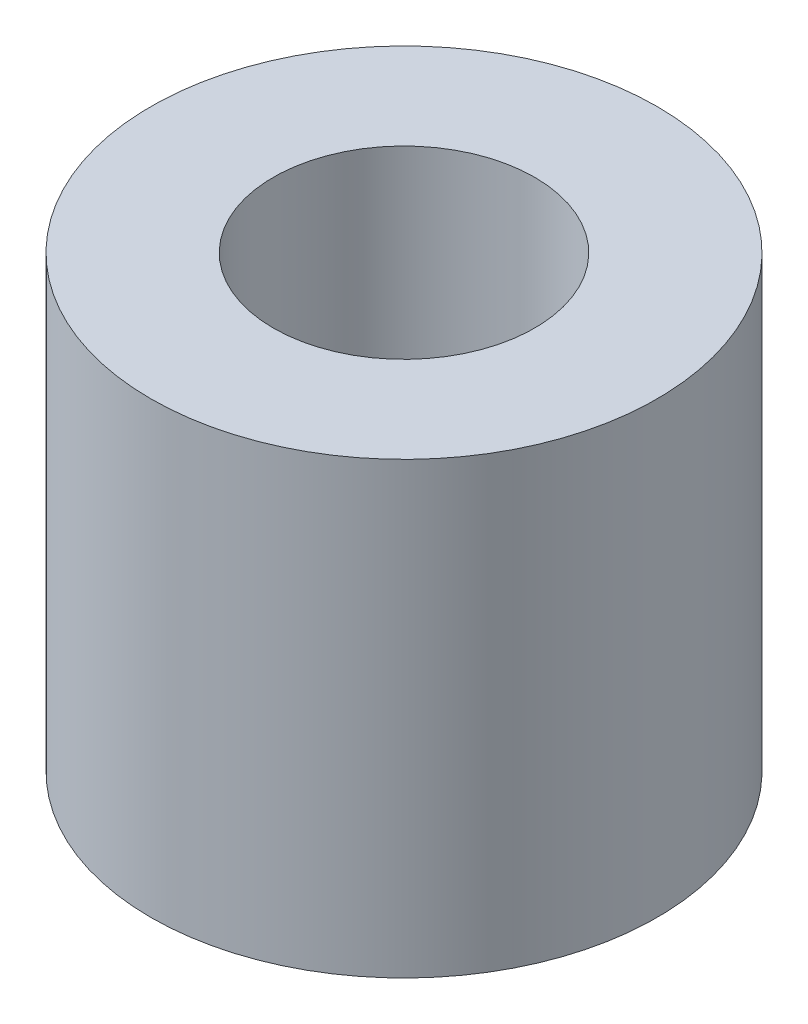
SolidWorks part; units mm, degrees
ref_plane "前视基准面" through (0, 0, 0) normal (0, 0, 1) x (1, 0, 0)
ref_plane "上视基准面" through (0, 0, 0) normal (0, 1, 0) x (1, 0, 0)
ref_plane "右视基准面" through (0, 0, 0) normal (1, 0, 0) x (0, 0, -1)
sketch "草图1" plane through (0, 0, 0) normal (0, 1, 0) x (1, 0, 0)
  circle A0 centre (0, 0) radius 1.6
  circle A1 centre (0, 0) radius 3.1
  dimension "D1" = 3.2
  dimension "D2" = 1.5
  dimension "D3" = 6.2
extrude "凸台-拉伸1" add sketch "草图1" along normal blind 5.5
